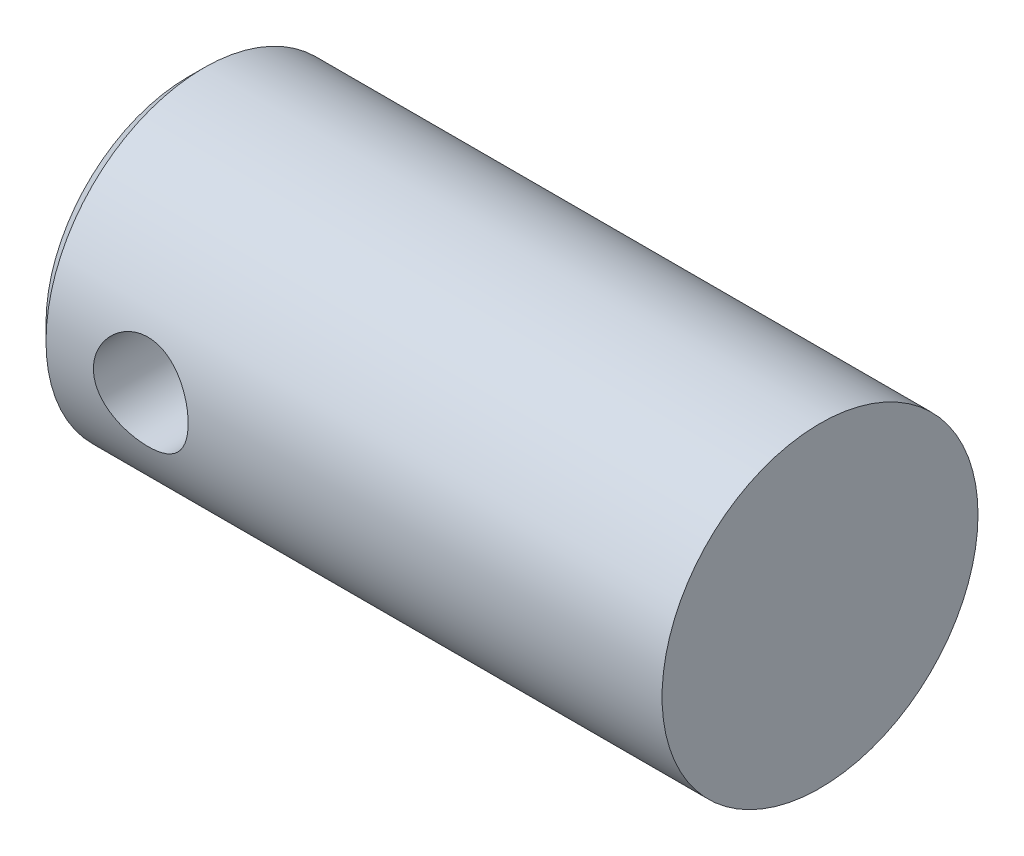
SolidWorks part; units mm, degrees
ref_plane "Plan1" through (0, 0, 0) normal (0, 0, 1) x (1, 0, 0)
ref_plane "Plan2" through (0, 0, 0) normal (0, 1, 0) x (1, 0, 0)
ref_plane "Plan3" through (0, 0, 0) normal (1, 0, 0) x (0, 0, -1)
sketch "Esquisse1" plane through (0, 0, 0) normal (0, 0, 1) x (1, 0, 0)
  line L0 (-20, 0) -> (-20, 5)
  line L1 (-20, 5) -> (0, 5)
  line L2 (0, 5) -> (0, 0)
  line L5 (0, 0) -> (-40, 0) construction
  line L6 (-20, 0) -> (0, 0)
  dimension "D1" = 20
  dimension "D2" = 10
revolve "Base-Révolution" add sketch "Esquisse1" angle 360 about L5
chamfer "Chanfrein1" distance 0.5 angle 45 1 edges at (-20, 0, -5)
sketch "Esquisse2" plane through (0, 0, 0) normal (0, 0, 1) x (1, 0, 0)
  circle A0 centre (-16.5, 0) radius 1.5
  dimension "D1" = 3
  dimension "D2" = 16.5
extrude "Extrusion1" cut sketch "Esquisse2" against normal through all and the other way through all
